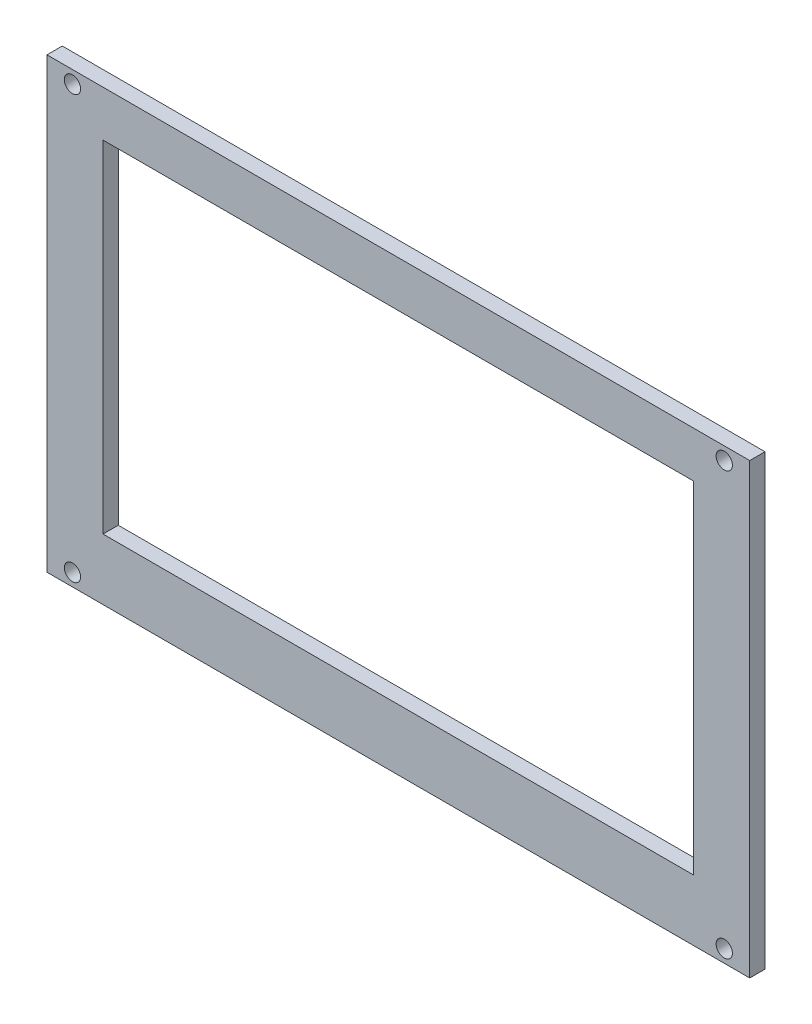
SolidWorks part; units mm, degrees
ref_plane "Alzado" through (0, 0, 0) normal (0, 0, 1) x (1, 0, 0)
ref_plane "Planta" through (0, 0, 0) normal (0, 1, 0) x (1, 0, 0)
ref_plane "Vista lateral" through (0, 0, 0) normal (1, 0, 0) x (0, 0, -1)
sketch "Croquis1" plane through (0, 0, 0) normal (0, 0, 1) x (1, 0, 0)
  line L1 (0, 88) -> (138, 88)
  line L2 (0, 88) -> (0, 0)
  line L3 (0, 0) -> (138, 0)
  line L4 (138, 88) -> (138, 0)
  dimension "D1" = 138
  dimension "D2" = 88
extrude "Saliente-Extruir1" add sketch "Croquis1" along normal blind 3
sketch "Croquis2" plane through (0, 0, 3) normal (0, 0, 1) x (1, 0, 0)
  line L0 (138, 88) -> (0, 88) construction
  line L1 (11, 79) -> (127, 79)
  line L2 (11, 79) -> (11, 12)
  line L3 (11, 12) -> (127, 12)
  line L4 (127, 79) -> (127, 12)
  line L5 (0, 0) -> (138, 0) construction
  line L6 (138, 0) -> (138, 88) construction
  line L7 (0, 88) -> (0, 0) construction
  dimension "D1" = 9
  dimension "D2" = 12
  dimension "D3" = 11
  dimension "D4" = 11
extrude "Cortar-Extruir1" cut sketch "Croquis2" against normal up to next
sketch "Croquis3" plane through (0, 0, 3) normal (0, 0, 1) x (1, 0, 0)
  line L0 (0, 85.5) -> (138, 85.5) construction
  line L1 (0, 88) -> (0, 0) construction
  line L2 (138, 0) -> (138, 88) construction
  line L3 (0, 2.5) -> (138, 2.5) construction
  line L4 (5, 88) -> (5, 0) construction
  line L5 (138, 88) -> (0, 88) construction
  line L6 (0, 0) -> (138, 0) construction
  line L7 (133, 88) -> (133, 0) construction
  dimension "D1" = 2.5
  dimension "D2" = 5
  dimension "D3" = 5
  dimension "D4" = 2.5
hole_wizard "Taladro de margen para M31" positions "Croquis3D1" profile "Croquis4" hole size "M3" standard "ISO" end condition up to next
sketch3d "Croquis3D1"
  line L0 (0, 85.5, 3) -> (138, 85.5, 3) construction
  line L1 (5, 88, 3) -> (5, 0, 3) construction
  line L2 (133, 88, 3) -> (133, 0, 3) construction
  line L3 (0, 2.5, 3) -> (138, 2.5, 3) construction
  point P0 (5, 85.5, 3)
  point P6 (133, 85.5, 3)
  point P10 (133, 2.5, 3)
  point P14 (5, 2.5, 3)
sketch "Croquis4" plane through (5, 85.5, 3) normal (1, 0, 0) x (0, -1, 0)
  line L0 (0, 0) -> (0, 3)
  line L1 (0, 3) -> (1.6, 3)
  line L2 (1.6, 3) -> (1.6, 0)
  line L5 (1.6, 0) -> (0, 0)
  line L11 (0, -6.35) -> (0, 107.95) construction
  dimension "Diámetro de taladro hasta el siguiente" = 3.2
  dimension "Profundidad de taladro hasta el siguiente" = 3
